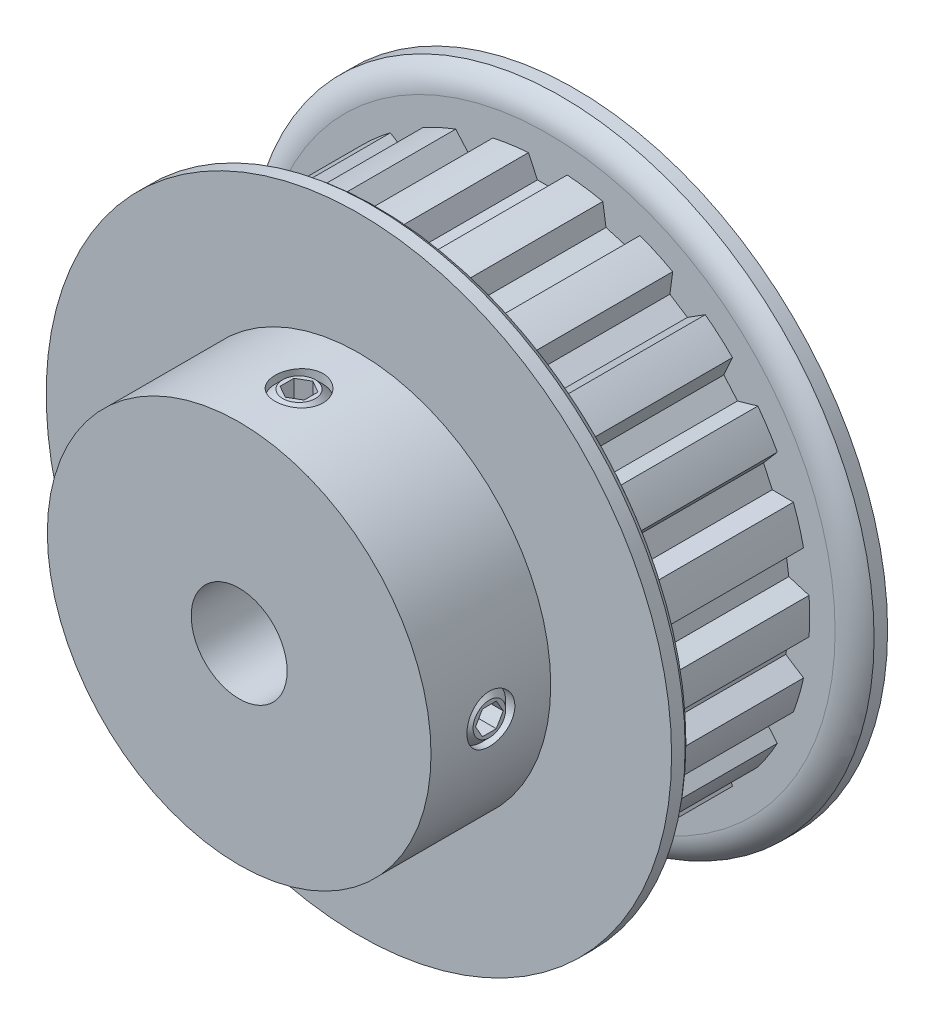
SolidWorks part; units mm, degrees
ref_plane "Front Plane" through (0, 0, 0) normal (0, 0, 1) x (1, 0, 0)
ref_plane "Top Plane" through (0, 0, 0) normal (0, 1, 0) x (1, 0, 0)
ref_plane "Right Plane" through (0, 0, 0) normal (1, 0, 0) x (0, 0, -1)
sketch "Sketch1" plane through (0, 0, 0) normal (0, 0, 1) x (1, 0, 0)
  line L0 (-1.2827, 17.2847) -> (-0.6905, 16.0147)
  line L1 (-0.6905, 16.0147) -> (0.6905, 16.0147)
  line L2 (0.6905, 16.0147) -> (1.2827, 17.2847)
  line L3 (-1.2827, 17.2847) -> (1.2827, 17.2847)
  line L4 (0, 0) -> (0, 16.0147) construction
  line L5 (0, 16.0147) -> (0, 18.3007) construction
  circle A0 centre (0, 0) radius 17.7927 construction
  circle A1 centre (0, 0) radius 20.701 construction
  circle A2 centre (0, 0) radius 17.3322 construction
  point P6 (0, 17.2847)
  point P11 (0, 17.7927)
  point P13 (0, 20.701)
  point P14 (0, 17.3322)
  dimension "D1" = 1.016
  dimension "PD" = 35.5854
  dimension "D2" = 0.508
  dimension "OD" = 41.402
  dimension "b" = 50
  dimension "bt" = 2.5654
  dimension "ht" = 1.27
  dimension "hs" = 2.286
sketch "Sketch2" plane through (0, 0, 0) normal (1, 0, 0) x (0, 0, -1)
  line L0 (-11.1125, 3.175) -> (11.1125, 3.175)
  line L1 (-11.1125, 3.175) -> (-11.1125, 12.7)
  line L2 (-11.1125, 12.7) -> (-3.1877, 12.7)
  line L3 (-3.1877, 12.7) -> (-3.1877, 20.701)
  line L4 (-3.1877, 20.701) -> (-1.397, 20.701) construction
  line L5 (-1.397, 20.701) -> (-1.397, 17.3322) construction
  line L6 (-1.397, 17.3322) -> (9.3218, 17.3322)
  line L7 (9.3218, 17.3322) -> (9.3218, 20.701) construction
  line L8 (9.3218, 20.701) -> (11.1125, 20.701) construction
  line L9 (11.1125, 20.701) -> (11.1125, 3.175)
  line L10 (-11.1125, 0) -> (11.1125, 0) construction
  line L13 (-3.1877, 20.701) -> (-2.2923, 20.701)
  line L14 (-1.397, 19.0166) -> (-1.397, 17.3322)
  line L15 (9.3218, 17.3322) -> (9.3218, 19.0166)
  line L16 (10.2172, 20.701) -> (11.1125, 20.701)
  arc A0 (-1.397, 19.0166) -> (-2.2923, 20.701) centre (-3.4291, 19.0166) ccw
  arc A1 (9.3218, 19.0166) -> (10.2172, 20.701) centre (11.3539, 19.0166) cw
  point P12 (-1.397, 19.0166)
  point P14 (-2.2923, 20.701)
  point P20 (9.3218, 19.0166)
  point P21 (10.2172, 20.701)
  point P25 (9.3218, 0)
  point P26 (-1.397, 0)
  dimension "OA" = 22.225
  dimension "Bore" = 6.35
  dimension "Hub Dia" = 25.4
  dimension "Outside Width" = 14.3002
  dimension "Inside Width" = 10.7188
revolve "Revolve1" add sketch "Sketch2" angle 360 mid plane about L10
sketch "Sketch3" plane through (0, 0, 0) normal (0, 0, 1) x (1, 0, 0)
  line L0 (-0.6905, 16.0147) -> (0.6905, 16.0147) construction
  line L1 (0.6905, 16.0147) -> (1.2827, 17.2847) construction
  line L2 (-1.2827, 17.2847) -> (-0.6905, 16.0147) construction
  line L3 (-0.6905, 16.0147) -> (0.6905, 16.0147)
  line L4 (0.6905, 16.0147) -> (1.2827, 17.2847)
  line L5 (-1.2827, 17.2847) -> (-0.6905, 16.0147)
  circle A0 centre (0, 0) radius 17.3322 construction
  arc A1 (1.2827, 17.2847) -> (-1.2827, 17.2847) centre (0, 0) ccw
extrude "Cut-Extrude1" cut sketch "Sketch3" against normal up to vertex (9.3218 mm away) from vertex at 1.397 starting at point (0, 17.3322, 1.397)
pattern_circular "CirPattern1" count 22 over 360 about axis through (0, 0, 0) along (0, 0, 1) of "Cut-Extrude1"
sketch "Sketch4" plane through (0, 0, 0) normal (0, 1, 0) x (1, 0, 0)
  line L0 (0, -3.1877) -> (0, -11.1125) construction
  line L1 (-12.7, -3.1877) -> (12.7, -3.1877) construction
  line L2 (-12.7, -11.1125) -> (12.7, -11.1125) construction
  circle A0 centre (0, -7.1501) radius 1.5875
  dimension "D1" = 3.175
extrude "Cut-Extrude2" cut sketch "Sketch4" along normal through all
ref_plane "Plane1" through (0, 0, 7.1501) normal (0, 0, 1) x (1, 0, 0)
sketch "Sketch5" plane through (0, 0, 7.1501) normal (0, 0, 1) x (1, 0, 0)
  line L0 (0, 0) -> (0, 12.7) construction
  line L1 (1.0795, 12.6004) -> (1.5875, 12.0924)
  line L2 (0, 12.6004) -> (1.0795, 12.6004)
  line L3 (0, 12.6004) -> (0, 3.175)
  line L4 (0, 3.175) -> (0.9525, 3.175)
  line L5 (1.5875, 12.0924) -> (1.5875, 3.81)
  line L6 (0.9525, 3.175) -> (1.5875, 3.81)
  circle A0 centre (0, 0) radius 12.7 construction
  circle A1 centre (0, 0) radius 3.175 construction
  point P7 (1.5875, 3.175)
  point P9 (1.5875, 12.6004)
revolve "Revolve2" add sketch "Sketch5" angle 360 mid plane about L0
sketch "Sketch6" plane through (0, 12.6004, 0) normal (0, 1, 0) x (1, 0, 0)
  line L1 (0, -6.2336) -> (-0.7938, -6.6918)
  line L2 (-0.7938, -6.6918) -> (-0.7937, -7.6084)
  line L3 (-0.7937, -7.6084) -> (0, -8.0666)
  line L4 (0, -8.0666) -> (0.7938, -7.6084)
  line L5 (0.7938, -7.6084) -> (0.7938, -6.6918)
  line L6 (0.7938, -6.6918) -> (0, -6.2336)
  circle A0 centre (0, -7.1501) radius 0.7938 construction
  dimension "D1" = 1.5875
extrude "Cut-Extrude3" cut sketch "Sketch6" against normal blind 1.1906
pattern_circular "CirPattern2" count 2 every 90 about axis through (0, 0, 0) along (0, 0, 1) of "Cut-Extrude2", "Revolve2", "Cut-Extrude3"
equation "\"D2@Sketch1\" = \"D1@Sketch1\"/2"
equation "\"D1@Sketch4\" = \"Bore@Sketch2\"/2"
equation "\"D1@Sketch6\" = \"D1@Sketch4\"/2"
equation "\"D1@Cut-Extrude3\" = \"D1@Sketch6\"*.75"
